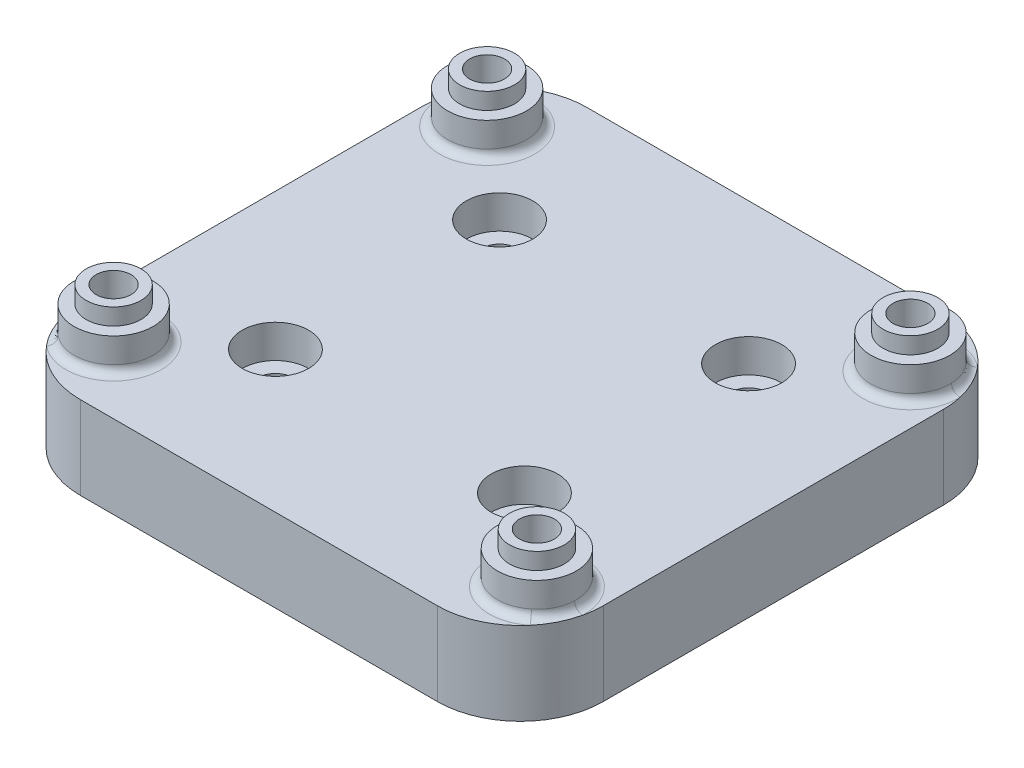
SolidWorks part; units mm, degrees
ref_plane "Plan de face" through (0, 0, 0) normal (0, 0, 1) x (1, 0, 0)
ref_plane "Plan de dessus" through (0, 0, 0) normal (0, 1, 0) x (1, 0, 0)
ref_plane "Plan de droite" through (0, 0, 0) normal (1, 0, 0) x (0, 0, -1)
sketch "Esquisse1" plane through (0, 0, 0) normal (0, 1, 0) x (1, 0, 0)
  line L1 (0, 0) -> (63, 0)
  line L2 (0, 0) -> (0, 61)
  line L3 (0, 61) -> (63, 61)
  line L4 (63, 0) -> (63, 61)
  dimension "D1" = 63
  dimension "D2" = 61
extrude "Boss.-Extru.1" add sketch "Esquisse1" along normal blind 10
sketch "Esquisse4" plane through (0, 10, 0) normal (0, 1, 0) x (1, 0, 0)
  line L0 (0, 61) -> (0, 0) construction
  line L1 (0, 0) -> (63, 0) construction
  circle A0 centre (6, 8) radius 4.75
  circle A1 centre (6, 53) radius 4.75
  circle A2 centre (57, 8) radius 4.75
  circle A3 centre (57, 53) radius 4.75
  dimension "D1" = 9.5
  dimension "D2" = 9.5
  dimension "D3" = 9.5
  dimension "D4" = 9.5
  dimension "D5" = 45
  dimension "D6" = 51
  dimension "D7" = 51
  dimension "D8" = 45
  dimension "D9" = 6
  dimension "D10" = 8
extrude "Boss.-Extru.3" add sketch "Esquisse4" along normal blind 4
sketch "Esquisse5" plane through (0, 14, 0) normal (0, 1, 0) x (1, 0, 0)
  circle A0 centre (57, 53) radius 3.3
  circle A1 centre (57, 8) radius 3.3
  circle A2 centre (6, 8) radius 3.3
  circle A3 centre (6, 53) radius 3.3
  dimension "D1" = 6.6
  dimension "D2" = 6.6
  dimension "D3" = 6.6
  dimension "D4" = 6.6
extrude "Boss.-Extru.4" add sketch "Esquisse5" along normal blind 2
sketch "Esquisse6" plane through (0, 16, 0) normal (0, 1, 0) x (1, 0, 0)
  circle A0 centre (6, 8) radius 2.1
  circle A1 centre (6, 53) radius 2.1
  circle A2 centre (57, 53) radius 2.1
  circle A3 centre (57, 8) radius 2.1
  dimension "D1" = 4.2
  dimension "D2" = 4.2
  dimension "D3" = 4.2
  dimension "D4" = 4.2
extrude "Enlèv. mat.-Extru.2" cut sketch "Esquisse6" against normal through all
fillet "Congé1" radius 10 4 edges at (0, 5, 0) (0, 5, -61) (63, 5, -61) (63, 5, 0)
fillet "Congé2" radius 1 4 edges at (57, 10, -57.75) (6, 10, -57.75) (6, 10, -12.75) (57, 10, -12.75)
sketch "Esquisse7" plane through (0, 0, 0) normal (0, -1, 0) x (-1, 0, 0)
  line L1 (-63, 10) -> (-63, 51) construction
  line L2 (-53, 61) -> (-10, 61) construction
  circle A0 centre (-16.5, 17) radius 2.1
  circle A1 centre (-46.5, 17) radius 2.1
  circle A2 centre (-16.5, 44) radius 2.1
  circle A3 centre (-46.5, 44) radius 2.1
  dimension "D1" = 4.2
  dimension "D2" = 4.2
  dimension "D3" = 4.2
  dimension "D4" = 4.2
  dimension "D5" = 30
  dimension "D6" = 30
  dimension "D7" = 16.5
  dimension "D8" = 27
  dimension "D9" = 17
extrude "Enlèv. mat.-Extru.3" cut sketch "Esquisse7" against normal through all
sketch "Esquisse8" plane through (0, 10, 0) normal (0, 1, 0) x (1, 0, 0)
  circle A0 centre (16.5, 44) radius 4
  circle A1 centre (46.5, 44) radius 4
  circle A2 centre (46.5, 17) radius 4
  circle A3 centre (16.5, 17) radius 4
  dimension "D1" = 8
  dimension "D2" = 8
  dimension "D3" = 8
  dimension "D4" = 8
extrude "Enlèv. mat.-Extru.4" cut sketch "Esquisse8" against normal blind 4
sketch "Esquisse9" plane through (0, 0, 0) normal (0, -1, 0) x (-1, 0, 0)
  circle A0 centre (-57, 8) radius 4
  circle A1 centre (-57, 53) radius 4
  circle A2 centre (-6, 53) radius 4
  circle A3 centre (-6, 8) radius 4
  dimension "D1" = 8
  dimension "D2" = 8
  dimension "D3" = 8
  dimension "D4" = 8
extrude "Enlèv. mat.-Extru.5" cut sketch "Esquisse9" against normal blind 4.5
